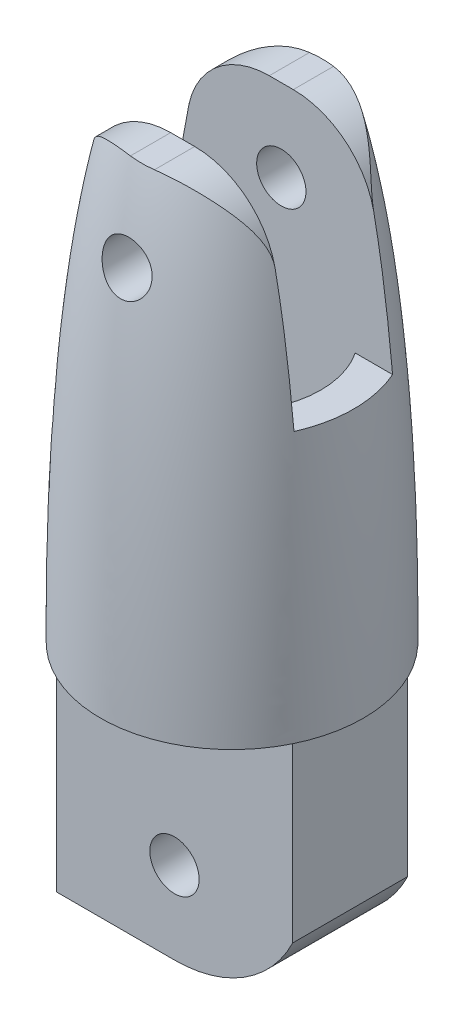
SolidWorks part; units mm, degrees
ref_plane "Front Plane" through (0, 0, 0) normal (0, 0, 1) x (1, 0, 0)
ref_plane "Top Plane" through (0, 0, 0) normal (0, 1, 0) x (1, 0, 0)
ref_plane "Right Plane" through (0, 0, 0) normal (1, 0, 0) x (0, 0, -1)
sketch "Sketch1" plane through (0, 0, 0) normal (1, 0, 0) x (0, 0, -1)
  line L0 (0, 0) -> (0, 28)
  line L1 (0, 0) -> (8, 0)
  line L2 (0, 28) -> (5.5, 28)
  line L3 (12.7758, 0.8465) -> (-1.7758, 55.1535) construction
  line L4 (8, -6.0162) -> (8, 6.0162) construction
  spline S0 degree 3 poles (5.5, 28) (8.0882, 18.3407) (8, 3.3333) (8, 0) knots 0 0 0 0 1 1 1 1
  dimension "D4" = 105
  dimension "D5" = 30
  dimension "D6" = 10
  dimension "D1" = 28
  dimension "D2" = 5.5
  dimension "D3" = 8
revolve "Revolve1" add sketch "Sketch1" angle 360 about L0
sketch "Sketch2" plane through (0, 0, 0) normal (1, 0, 0) x (0, 0, -1)
  line L0 (5.5, 28) -> (-5.5, 28) construction
  line L1 (-3, 28) -> (3, 28)
  line L2 (-3, 28) -> (-3, 16)
  line L3 (-3, 16) -> (3, 16)
  line L4 (3, 28) -> (3, 16)
  point P6 (0, 16)
  dimension "D1" = 6
  dimension "D2" = 12
extrude "Cut-Extrude1" cut sketch "Sketch2" against normal through all and the other way through all
sketch "Sketch3" plane through (0, 0, 0) normal (0, 0, 1) x (1, 0, 0)
  line L0 (-8, 0) -> (-8, -15)
  line L1 (-8, -15) -> (0, -15)
  line L2 (-8, 0) -> (8, 0)
  line L3 (8, 0) -> (8, -7)
  arc A0 (0, -15) -> (8, -7) centre (0, -7) ccw
  dimension "D1" = 15
  dimension "D2" = 7
extrude "Boss-Extrude1" add sketch "Sketch3" along normal mid plane 7
sketch "Sketch4" plane through (0, -15, 0) normal (0, -1, 0) x (1, 0, 0)
  line L0 (-7.1937, 3.5) -> (-7.1937, -3.5)
  line L1 (7.1937, 3.5) -> (7.1937, -3.5)
  line L3 (-7.1937, 3.5) -> (-8, 3.5)
  line L4 (-7.1937, 3.5) -> (-7.1937, -3.5)
  line L5 (-7.1937, -3.5) -> (-8, -3.5)
  line L6 (-8, 3.5) -> (-8, -3.5)
  line L7 (7.1937, 3.5) -> (8, 3.5)
  line L8 (7.1937, 3.5) -> (7.1937, -3.5)
  line L9 (7.1937, -3.5) -> (8, -3.5)
  line L10 (8, 3.5) -> (8, -3.5)
  line M2 (-8, -3.5) -> (0, -3.5)
  line M4 (0, 3.5) -> (-8, 3.5)
  line M5 (-8, 3.5) -> (-8, -3.5)
extrude "Cut-Extrude4" cut sketch "Sketch4" against normal blind 15 and the other way through all contours L0 M4 M5 M2 | L10 L7 L1 L9
sketch "Sketch5" plane through (0, 0, 0) normal (0, 0, 1) x (1, 0, 0)
  line L0 (4.6098, 28) -> (-4.6098, 28) construction
  line L1 (-7.1937, -15) -> (0, -15) construction
  circle A0 centre (0, 23) radius 1.5
  circle A1 centre (0, -10) radius 1.5
  dimension "D1" = 3
  dimension "D2" = 5
  dimension "D3" = 5
extrude "Cut-Extrude5" cut sketch "Sketch5" against normal blind 14 and the other way blind 14
sketch "Sketch6" plane through (0, 16, 0) normal (0, 1, 0) x (1, 0, 0)
  line L0 (-6.7743, -3) -> (6.7743, -3) construction
  line L1 (-6.7743, 3) -> (6.7743, 3) construction
  line L2 (-6.7743, -3) -> (6.7743, -3)
  line L3 (-6.7743, 3) -> (6.7743, 3)
  circle A0 centre (0, 0) radius 5.4088
  arc A2 (6.7743, -3) -> (6.7743, 3) centre (0, 0) ccw construction
  dimension "D1" = 2
extrude "Cut-Extrude6" cut sketch "Sketch6" against normal blind 12 contours L2 A0 L3
sketch "Sketch7" plane through (0, 0, 0) normal (0, 0, 1) x (1, 0, 0)
  line L0 (4.6098, 28) -> (-4.6098, 28) construction
  line L1 (4.6098, 28) -> (-4.6098, 28)
  arc A0 (-5.6302, 24.0006) -> (-0.7313, 28) centre (-0.7313, 23) cw
  arc A1 (0.7313, 28) -> (5.6302, 24.0006) centre (0.7313, 23) cw
  spline S2 degree 3 poles (-992.3567, -49.8104) (-47.0988, 85.652) (-2.2434, 58.7045) (5.6303, 24.0539) (5.8226, 23.0561) (16.9927, -43.0252) (-67.0973, -125.2564) (1006.6585, 1.3585) knots -8.233551 -8.233551 -8.233551 -8.233551 0.25 0.25 0.5 0.5 16.737586 16.737586 16.737586 16.737586 only from (4.6098, 28) to (6.7743, 16) construction
  spline S3 degree 3 poles (-1006.6669, 1.3595) (67.0978, -125.2568) (-16.9927, -43.0253) (-5.8226, 23.0561) (-5.6303, 24.0539) (2.2433, 58.7041) (47.0977, 85.6514) (992.3243, -49.8057) knots -15.737629 -15.737629 -15.737629 -15.737629 0.5 0.5 0.75 0.75 9.233454 9.233454 9.233454 9.233454 only from (-6.7743, 16) to (-4.6098, 28) construction
  spline S4 degree 3 poles (4.6098, 28) (4.9219, 27.0238) (5.1796, 26.0377) (5.6303, 24.0539) (5.8226, 23.0561) (6.3307, 20.0501) (6.5793, 18.0299) (6.7743, 16) knots 0 0 0 0 0.25 0.25 0.5 0.5 1 1 1 1
  spline S5 degree 3 poles (-6.7743, 16) (-6.5793, 18.0299) (-6.3307, 20.0501) (-5.8226, 23.0561) (-5.6303, 24.0539) (-5.1796, 26.0377) (-4.9219, 27.0238) (-4.6098, 28) knots 0 0 0 0 0.5 0.5 0.75 0.75 1 1 1 1
  point P10 (-0.9435, 23.3717)
  dimension "D1" = 5
extrude "Cut-Extrude7" cut sketch "Sketch7" against normal blind 18 from offset 10 contours S4 L1 A1 | S5 A0 L1
sketch "Sketch8" plane through (0, -15, 0) normal (0, -1, 0) x (1, 0, 0)
  line L0 (0, 3.5) -> (0, -3.5) construction
  circle A0 centre (3, 0) radius 1
  point P4 (0, 0)
  dimension "D2" = 2
  dimension "D1" = 3
extrude "Cut-Extrude8" cut sketch "Sketch8" against normal through all
sketch "Sketch9" plane through (-7.1937, 0, 0) normal (-1, 0, 0) x (0, 0, 1)
  line L0 (0, 0) -> (0, -15) construction
  line L1 (3.5, -15) -> (-3.5, -15) construction
  circle A0 centre (0, -7.5) radius 1
  point P7 (0, 0)
  point P8 (0, -7.5)
  dimension "D1" = 2
sketch "Sketch10" plane through (0, 0, 0) normal (0, 0, 1) x (1, 0, 0)
  line L1 (-7.1937, 0) -> (-7.1937, -15) construction
  line L2 (-7.1937, -7.5) -> (-2.6937, -7.5) construction
  line L3 (-2.6937, -7.5) -> (-2.6937, 4) construction
  line L6 (4, 4) -> (2, 4) construction
  spline S0 degree 2 poles (-7.1937, -7.5) (-2.6937, -7.5) (-2.6937, 4) knots 0 0 0 1 1 1
  point P1 (-2.3931, 0)
  point P2 (0, 0)
  dimension "D1" = 4.5
sweep "Cut-Sweep1" cut profiles "Sketch9" path "Sketch10"
